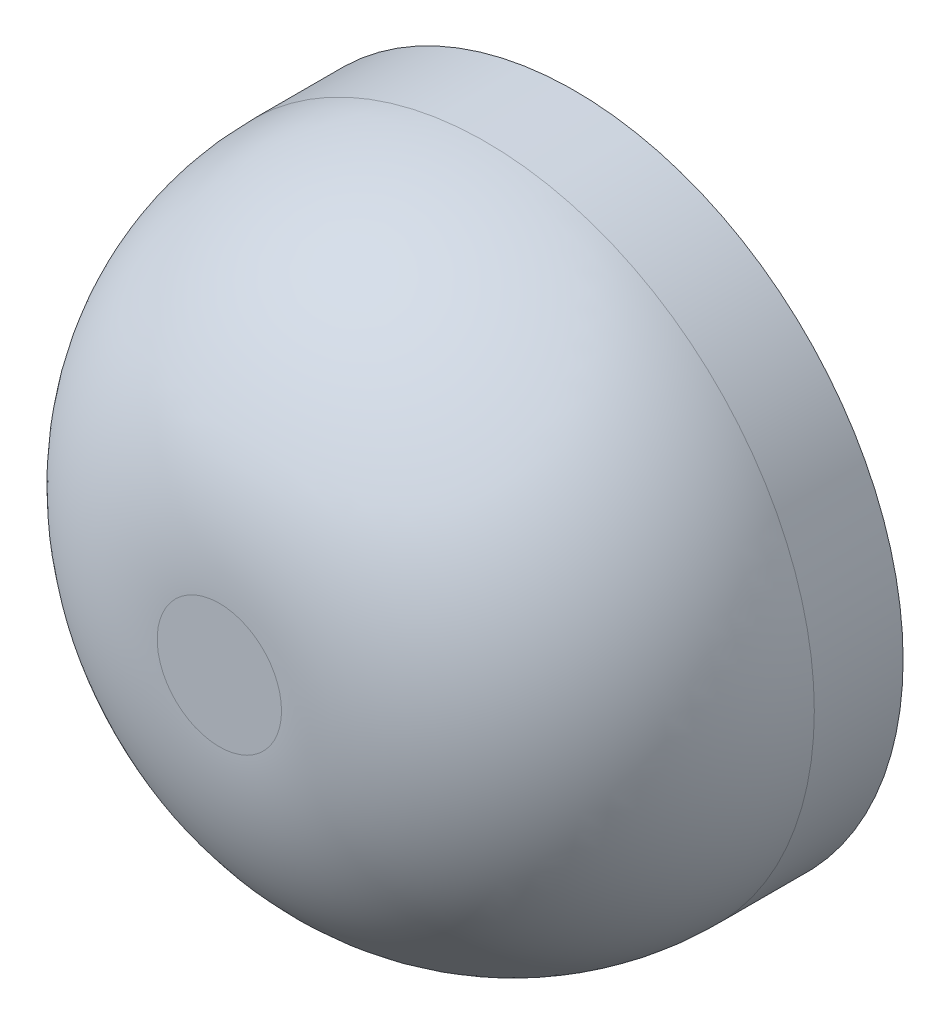
SolidWorks part; units mm, degrees
material "moto_glass_red"
ref_plane "Front Plane" through (0, 0, 0) normal (0, 0, 1) x (1, 0, 0)
ref_plane "Top Plane" through (0, 0, 0) normal (0, 1, 0) x (1, 0, 0)
ref_plane "Right Plane" through (0, 0, 0) normal (1, 0, 0) x (0, 0, -1)
sketch "Sketch1" plane through (0, 0, 0) normal (0, 0, 1) x (1, 0, 0)
  circle A0 centre (0, 0) radius 18.5
  dimension "D1" = 37
extrude "Boss-Extrude1" add sketch "Sketch1" along normal blind 20
fillet "Fillet1" radius 15 1 edges at (18.5, 0, 20)
shell "Shell1" thickness 2
